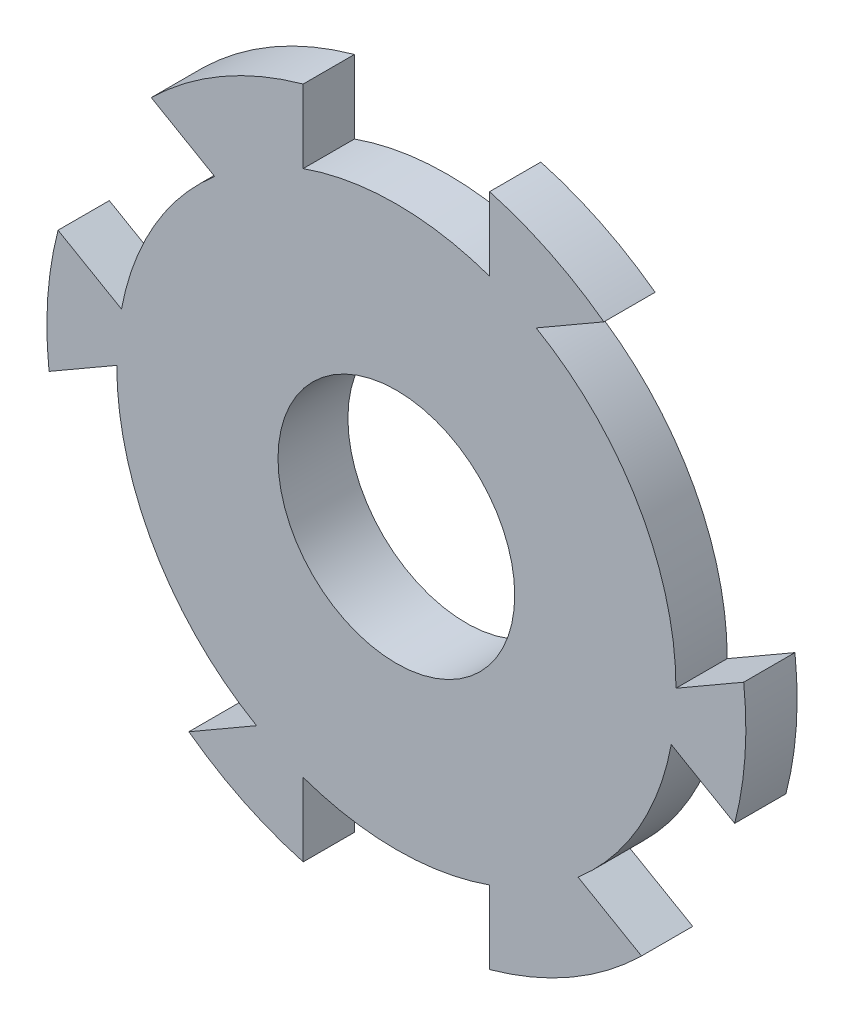
SolidWorks part; units mm, degrees
ref_plane "Front Plane" through (0, 0, 0) normal (0, 0, 1) x (1, 0, 0)
ref_plane "Top Plane" through (0, 0, 0) normal (0, 1, 0) x (1, 0, 0)
ref_plane "Right Plane" through (0, 0, 0) normal (1, 0, 0) x (0, 0, -1)
sketch "Sketch1" plane through (0, 0, 0) normal (0, 0, 1) x (1, 0, 0)
  line L0 (-7.4917, 1.3924) -> (-9.2202, 2.3903)
  line L1 (2.54, 7.1842) -> (2.54, 9.1801)
  line L2 (-2.54, 7.1842) -> (-2.54, 9.1801)
  line L3 (-4.9517, 5.7918) -> (-6.6802, 6.7897)
  line L5 (7.62, 0) -> (9.4652, 1.0653)
  line L6 (3.81, 6.5991) -> (5.6552, 7.6645)
  line L8 (2.54, -7.1842) -> (2.54, -9.1801)
  line L9 (-2.54, -7.1842) -> (-2.54, -9.1801)
  line L10 (7.4917, -1.3924) -> (9.2202, -2.3903)
  line L11 (-7.62, 0) -> (-9.4652, -1.0653)
  line L12 (-3.81, -6.5991) -> (-5.6552, -7.6645)
  line L13 (4.9517, -5.7918) -> (6.6802, -6.7897)
  arc A0 (-2.54, 9.1801) -> (-6.6802, 6.7897) centre (0, 0) ccw
  circle A1 centre (0, 0) radius 3.2258
  arc A2 (2.54, 7.1842) -> (-2.54, 7.1842) centre (0, 0) ccw
  arc A3 (-9.2202, 2.3903) -> (-9.4652, -1.0653) centre (0, 0) ccw
  arc A4 (-5.6552, -7.6645) -> (-2.54, -9.1801) centre (0, 0) ccw
  arc A5 (2.54, -9.1801) -> (6.6802, -6.7897) centre (0, 0) ccw
  arc A6 (9.2202, -2.3903) -> (9.4652, 1.0653) centre (0, 0) ccw
  arc A7 (5.6552, 7.6645) -> (2.54, 9.1801) centre (0, 0) ccw
  arc A8 (-4.9517, 5.7918) -> (-7.4917, 1.3924) centre (0, 0) ccw
  arc A9 (-7.62, 0) -> (-3.81, -6.5991) centre (0, 0) ccw
  arc A10 (-2.54, -7.1842) -> (2.54, -7.1842) centre (0, 0) ccw
  arc A11 (4.9517, -5.7918) -> (7.4917, -1.3924) centre (0, 0) ccw
  arc A12 (7.62, 0) -> (3.81, 6.5991) centre (0, 0) ccw
extrude "Extrude1" add sketch "Sketch1" along normal blind 1.397
sketch "Sketch2" plane through (0, 0, 0) normal (0, 0, -1) x (-1, 0, 0)
  circle A0 centre (0, 0) radius 3.2258
  circle A1 centre (0, 0) radius 4.7625
extrude "Extrude2" add sketch "Sketch2" along normal blind 0.508
